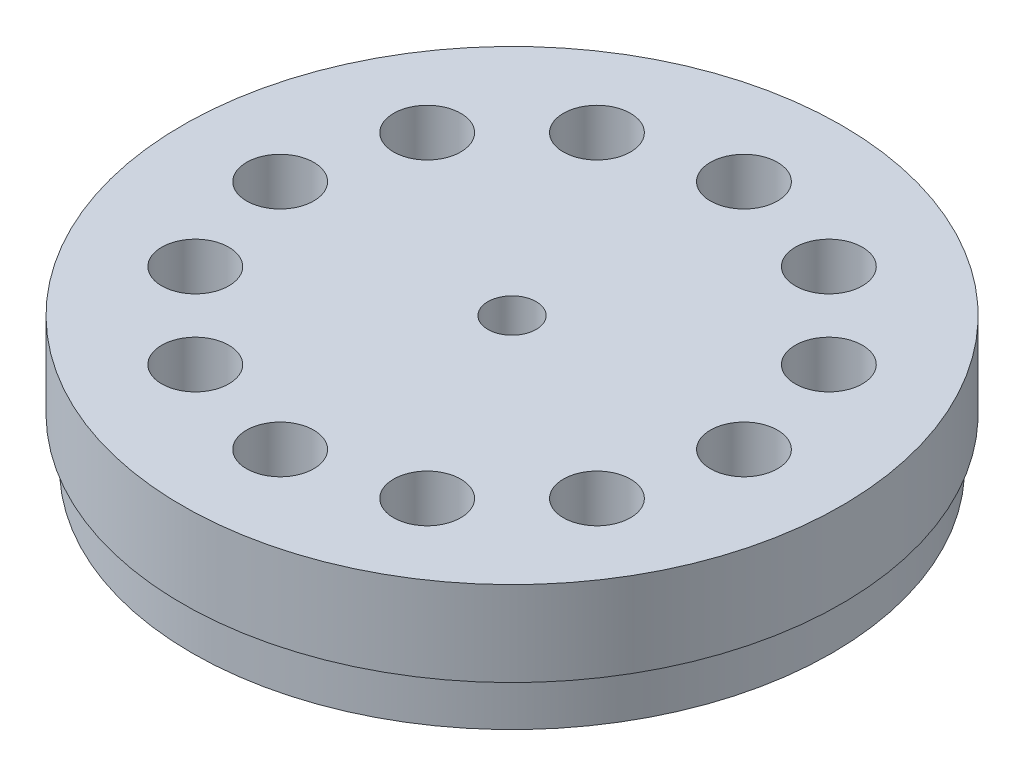
SolidWorks part; units mm, degrees
material "PVC Rigid"
ref_plane "Front Plane" through (0, 0, 0) normal (0, 0, 1) x (1, 0, 0)
ref_plane "Top Plane" through (0, 0, 0) normal (0, 1, 0) x (1, 0, 0)
ref_plane "Right Plane" through (0, 0, 0) normal (1, 0, 0) x (0, 0, -1)
sketch "Sketch1" plane through (0, 0, 0) normal (0, 0, 1) x (1, 0, 0)
  line L0 (0, 0) -> (-30.6832, 0)
  line L1 (-30.6832, 0) -> (-30.6832, -7.8994)
  line L2 (-30.6832, -7.8994) -> (-29.7942, -7.8994)
  line L3 (-29.7942, -7.8994) -> (-29.7942, -12.319)
  line L4 (-29.7942, -12.319) -> (-26.1112, -12.319)
  line L5 (-26.1112, -12.319) -> (-26.1112, -6.223)
  line L6 (-26.1112, -6.223) -> (0, -6.223)
  line L7 (0, -6.223) -> (0, 0)
  dimension "D1" = 7.8994
  dimension "D2" = 12.319
  dimension "D3" = 0.889
  dimension "D4" = 3.683
  dimension "D5" = 30.6832
  dimension "D6" = 6.096
revolve "Revolve1" add sketch "Sketch1" angle 360 about L7
sketch "Sketch2" plane through (0, 0, 0) normal (0, 1, 0) x (1, 0, 0)
  line L0 (0, 0) -> (0, 21.59) construction
  dimension "D1" = 21.59
hole_wizard "D (0.246) Diameter Hole1" positions "3DSketch1" profile "Sketch3" hole size "D" standard "Ansi Inch"
sketch3d "3DSketch1"
  point P0 (0, 0, -21.59)
sketch "Sketch3" plane through (0, 0, -21.59) normal (1, 0, 0) x (0, 0, 1)
  line L0 (0, 0) -> (0, 14.5772)
  line L1 (0, 14.5772) -> (3.1242, 12.7)
  line L2 (3.1242, 12.7) -> (3.1242, 0)
  line L5 (3.1242, 0) -> (0, 0)
  line L10 (0, 14.5772) -> (-3.1242, 12.7) construction
  line L11 (0, -6.35) -> (0, 107.95) construction
  dimension "Hole Dia." = 6.2484
  dimension "Hole Depth" = 12.7
  dimension "Drill Angle" = 118
pattern_circular "CirPattern1" count 12 over 360 about axis through (0, 0, 0) along (0, 1, 0) of "D (0.246) Diameter Hole1"
hole_wizard "#8 Clearance Hole1" positions "Sketch6" profile "Sketch5" hole size "#8" standard "Ansi Inch"
sketch "Sketch6" plane through (0, -6.223, 0) normal (0, -1, 0) x (1, 0, 0)
  point P1 (0, 0)
sketch "Sketch5" plane through (0, -6.223, 0) normal (1, 0, 0) x (0, 0, -1)
  line L0 (0, 0) -> (0, 11.0027)
  line L1 (0, 11.0027) -> (2.2479, 9.652)
  line L2 (2.2479, 9.652) -> (2.2479, 0)
  line L5 (2.2479, 0) -> (0, 0)
  line L10 (0, 11.0027) -> (-2.2479, 9.652) construction
  line L11 (0, -6.35) -> (0, 107.95) construction
  dimension "Hole Dia." = 4.4958
  dimension "Hole Depth" = 9.652
  dimension "Drill Angle" = 118
